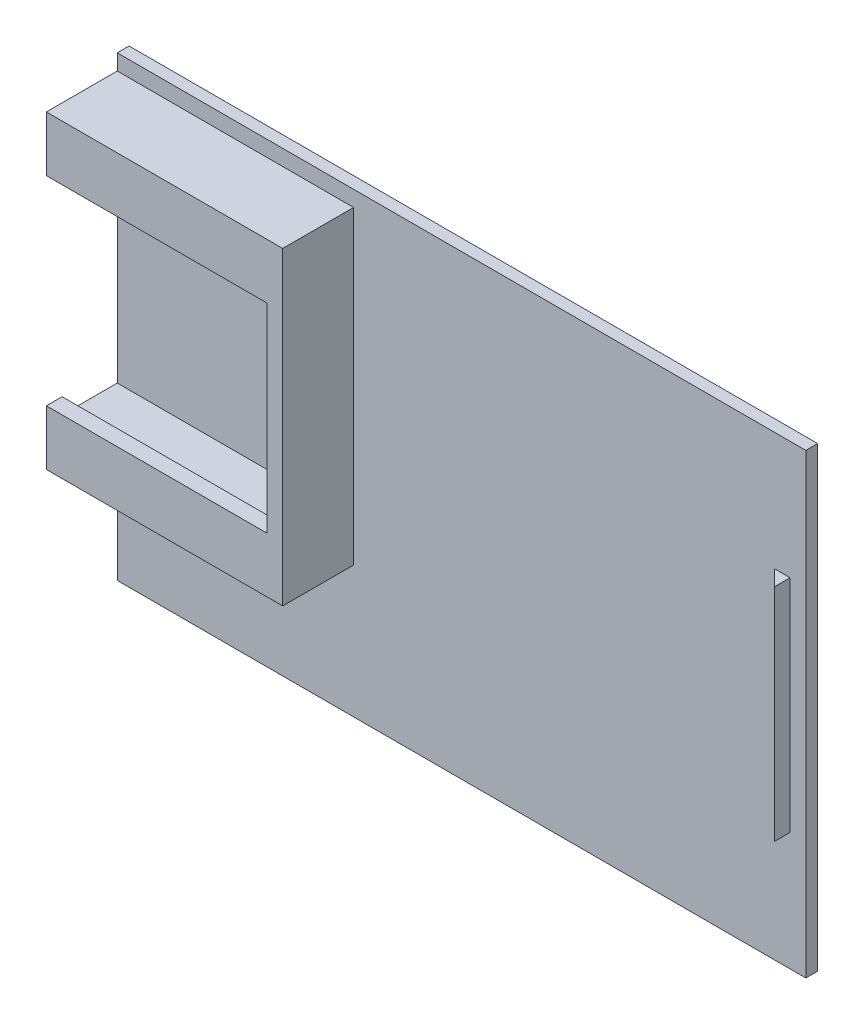
SolidWorks part; units mm, degrees
ref_plane "前视基准面" through (0, 0, 0) normal (0, 0, 1) x (1, 0, 0)
ref_plane "上视基准面" through (0, 0, 0) normal (0, 1, 0) x (1, 0, 0)
ref_plane "右视基准面" through (0, 0, 0) normal (1, 0, 0) x (0, 0, -1)
sketch "草图1" plane through (0, 0, 0) normal (0, 0, 1) x (1, 0, 0)
  line L1 (-43.7, 29) -> (43.7, 29)
  line L2 (-43.7, 29) -> (-43.7, -29)
  line L3 (-43.7, -29) -> (43.7, -29)
  line L4 (43.7, 29) -> (43.7, -29)
  line L5 (-43.7, 29) -> (43.7, -29) construction
  line L6 (-43.7, -29) -> (43.7, 29) construction
  point P0 (0, 0)
  dimension "D1" = 87.4
  dimension "D2" = 58
extrude "凸台-拉伸1" add sketch "草图1" along normal blind 2
sketch "草图2" plane through (0, 0, 2) normal (0, 0, 1) x (1, 0, 0)
  line L0 (-43.7, 29) -> (-43.7, -29) construction
  line L1 (-43.7, -27) -> (-13.7, -27)
  line L2 (-43.7, -27) -> (-43.7, -25)
  line L3 (-43.7, -25) -> (-13.7, -25)
  line L4 (-13.7, -27) -> (-13.7, -25)
  line L5 (-43.7, -29) -> (43.7, -29) construction
  line L7 (-13.7, -27) -> (-15.7, -27)
  line L8 (-13.7, -27) -> (-13.7, 12.3)
  line L9 (-13.7, 12.3) -> (-15.7, 12.3)
  line L10 (-15.7, -27) -> (-15.7, 12.3)
  line L11 (-13.7, 12.3) -> (-43.7, 12.3)
  line L12 (-13.7, 12.3) -> (-13.7, 10.3)
  line L13 (-13.7, 10.3) -> (-43.7, 10.3)
  line L14 (-43.7, 12.3) -> (-43.7, 10.3)
  line M11 (-43.7, 29) -> (-43.7, -29)
  dimension "D1" = 2
  dimension "D2" = 30
  dimension "D3" = 2
  dimension "D4" = 2
  dimension "D5" = 39.3
  dimension "D6" = 2
  dimension "D7" = 35.3
extrude "凸台-拉伸2" add sketch "草图2" along normal blind 9 contours L8 L13 L10 L3 | L13 L10 L11 M11 | L1 L10 L3 M11 | L13 L8 L9 L10
sketch "草图3" plane through (-15.7, 0, 0) normal (-1, 0, 0) x (0, 0, 1)
  line L1 (11, 10.3) -> (9, 10.3)
  line L2 (11, 10.3) -> (11, 5.3)
  line L3 (11, 5.3) -> (9, 5.3)
  line L4 (9, 10.3) -> (9, 5.3)
  line L5 (11, -25) -> (9, -25)
  line L6 (11, -25) -> (11, -20)
  line L7 (11, -20) -> (9, -20)
  line L8 (9, -25) -> (9, -20)
  dimension "D1" = 5
  dimension "D2" = 2
  dimension "D3" = 2
  dimension "D4" = 5
extrude "凸台-拉伸3" add sketch "草图3" along normal blind 28
sketch "草图4" plane through (0, 0, 2) normal (0, 0, 1) x (1, 0, 0)
  line L0 (-43.7, 10.3) -> (-43.7, -25) construction
  line L1 (-15.7, 10.3) -> (-43.7, 10.3)
  line L2 (-15.7, 10.3) -> (-15.7, 7.3)
  line L3 (-15.7, 7.3) -> (-43.7, 7.3)
  line L4 (-43.7, 10.3) -> (-43.7, 7.3)
  line L6 (-15.7, -25) -> (-43.7, -25)
  line L7 (-15.7, -25) -> (-15.7, -22)
  line L8 (-15.7, -22) -> (-43.7, -22)
  line L9 (-43.7, -25) -> (-43.7, -22)
  dimension "D1" = 3
  dimension "D2" = 3
extrude "凸台-拉伸4" add sketch "草图4" along normal blind 5.4
sketch "草图5" plane through (0, -29, 0) normal (0, -1, 0) x (1, 0, 0)
  line L0 (39.7, 2) -> (41.7, 4)
  line L1 (-43.7, 2) -> (43.7, 2) construction
  line L2 (41.7, 4) -> (41.7, 2)
  line L3 (41.7, 2) -> (39.7, 2)
  line L4 (43.7, 2) -> (43.7, 0) construction
  dimension "D1" = 2
  dimension "D2" = 2
  dimension "D3" = 2
extrude "凸台-拉伸7" add sketch "草图5" against normal blind 58
sketch "草图6" plane through (0, 0, 2) normal (0, 0, 1) x (1, 0, 0)
  line L1 (43.7, -29) -> (29.3767, -29)
  line L2 (43.7, -29) -> (43.7, -14)
  line L3 (43.7, -14) -> (29.3767, -14)
  line L4 (29.3767, -29) -> (29.3767, -14)
  line L5 (43.7, 29) -> (29.3767, 29)
  line L6 (43.7, 29) -> (43.7, 14)
  line L7 (43.7, 14) -> (29.3767, 14)
  line L8 (29.3767, 29) -> (29.3767, 14)
  dimension "D1" = 15
  dimension "D2" = 15
extrude "切除-拉伸2" cut sketch "草图6" along normal blind 58
sketch "草图8" plane through (0, 0, 2) normal (0, 0, 1) x (1, 0, 0)
  line L0 (-43.7, 29) -> (-43.7, 12.3) construction
  line L1 (-43.7, 14.3) -> (43.7, 14.3)
  line L2 (-43.7, 14.3) -> (-43.7, -43.7)
  line L3 (-43.7, -43.7) -> (43.7, -43.7)
  line L4 (43.7, 14.3) -> (43.7, -43.7)
  line L5 (43.7, -29) -> (43.7, 29) construction
  line L6 (-13.7, 12.3) -> (-43.7, 12.3) construction
  line L8 (-43.7, 14.3) -> (43.7, 14.3)
  line L9 (-43.7, 14.3) -> (-43.7, 29)
  line L10 (-43.7, 29) -> (43.7, 29)
  line L11 (43.7, 14.3) -> (43.7, 29)
  line M9 (43.7, 29) -> (-43.7, 29)
  line M10 (-43.7, 29) -> (-43.7, 12.3)
  line M16 (43.7, -29) -> (43.7, 29)
  dimension "D1" = 2
  dimension "D2" = 58
extrude "切除-拉伸3" cut sketch "草图8" against normal blind 35 contours L1 M10 M16 M9
sketch "草图9" plane through (0, 0, 0) normal (0, 0, -1) x (-1, 0, 0)
  line L0 (-43.7, -29) -> (-43.7, 14.3) construction
  line L1 (43.7, 14.3) -> (-43.7, 14.3)
  line L2 (43.7, 14.3) -> (43.7, -43.7)
  line L3 (43.7, -43.7) -> (-43.7, -43.7)
  line L4 (-43.7, 14.3) -> (-43.7, -43.7)
  dimension "D1" = 58
extrude "凸台-拉伸8" add sketch "草图9" against normal blind 2
sketch "草图10" plane through (0, -14, 0) normal (0, -1, 0) x (1, 0, 0)
  line L0 (41.7, 4) -> (41.7, 2)
  line L1 (41.7, 2) -> (39.7, 2)
  line L2 (39.7, 2) -> (41.7, 4)
extrude "凸台-拉伸9" add sketch "草图10" along normal blind 29
sketch "草图11" plane through (0, 0, 2) normal (0, 0, 1) x (1, 0, 0)
  line L1 (43.7, 14.3) -> (34.8878, 14.3)
  line L2 (43.7, 14.3) -> (43.7, -0.7)
  line L3 (43.7, -0.7) -> (34.8878, -0.7)
  line L4 (34.8878, 14.3) -> (34.8878, -0.7)
  line L5 (43.7, -43.7) -> (34.8878, -43.7)
  line L6 (43.7, -43.7) -> (43.7, -28.7)
  line L7 (43.7, -28.7) -> (34.8878, -28.7)
  line L8 (34.8878, -43.7) -> (34.8878, -28.7)
  dimension "D1" = 15
  dimension "D2" = 15
extrude "切除-拉伸4" cut sketch "草图11" along normal blind 13
sketch "草图13" plane through (0, 14.3, 0) normal (0, 1, 0) x (1, 0, 0)
  line L0 (43.7, 0) -> (43.7, -2) construction
  line L1 (-43.7, 0) -> (43.7, 0)
  line L2 (-43.7, 0) -> (-43.7, -0.5)
  line L3 (-43.7, -0.5) -> (43.7, -0.5)
  line L4 (43.7, 0) -> (43.7, -0.5)
  dimension "D1" = 0.5
extrude "切除-拉伸6" cut sketch "草图13" against normal blind 200
